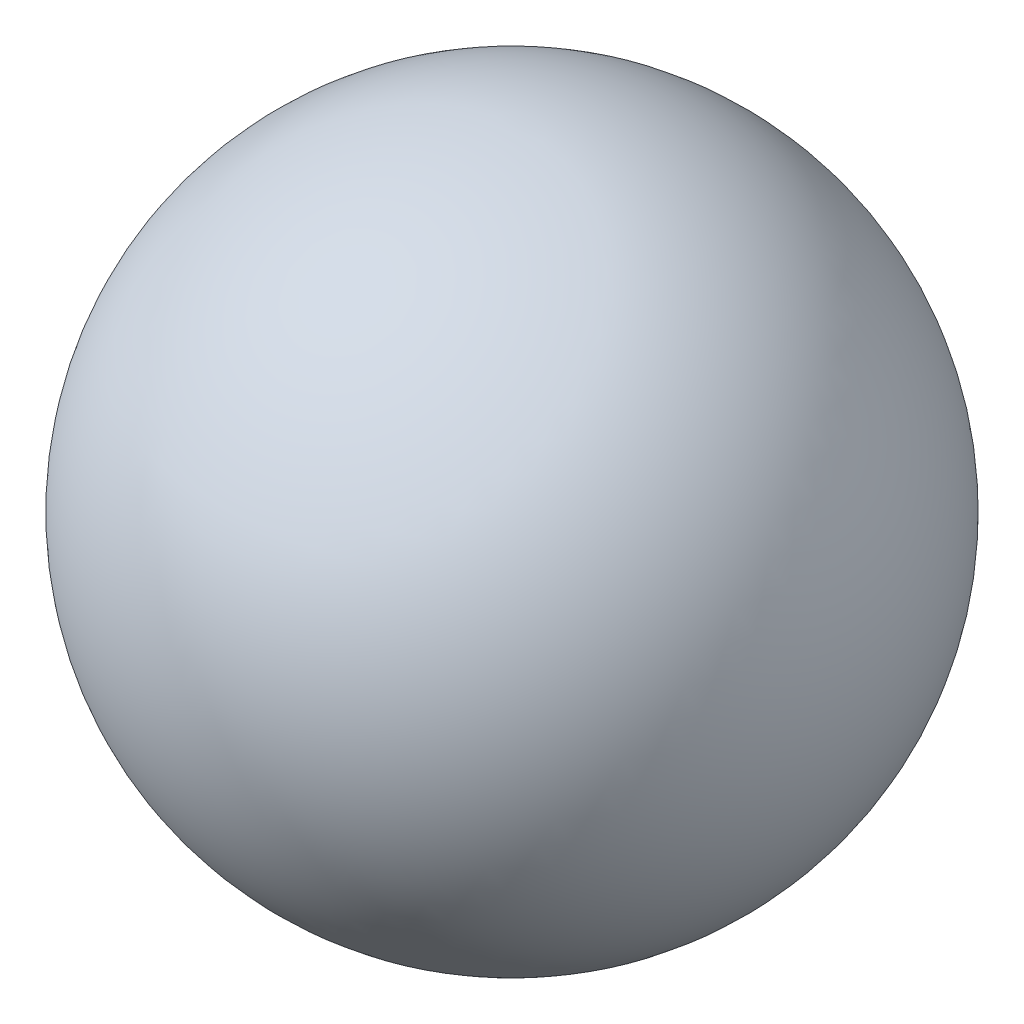
SolidWorks part; units mm, degrees
ref_plane "Front Plane" through (0, 0, 0) normal (0, 0, 1) x (1, 0, 0)
ref_plane "Top Plane" through (0, 0, 0) normal (0, 1, 0) x (1, 0, 0)
ref_plane "Right Plane" through (0, 0, 0) normal (1, 0, 0) x (0, 0, -1)
sketch "Sketch1" plane through (0, 0, 0) normal (1, 0, 0) x (0, 0, -1)
  line L0 (0, 4) -> (0, -4)
  arc A0 (0, 4) -> (0, -4) centre (0, 0) ccw
  point P5 (0, 0)
  dimension "D1" = 8
revolve "Revolve1" add sketch "Sketch1" angle 360 about L0
